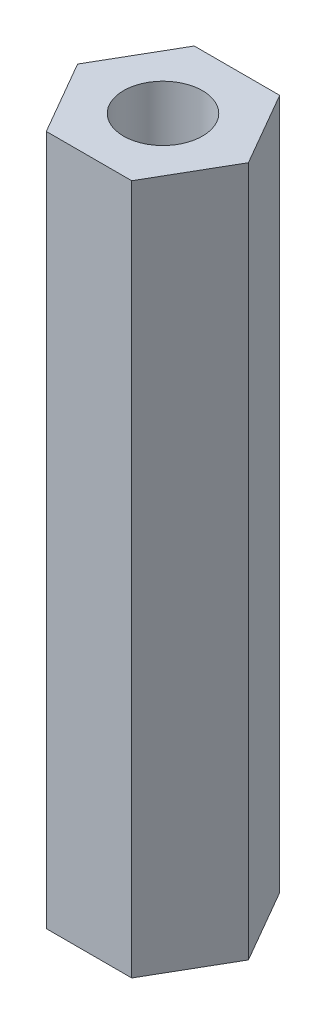
SolidWorks part; units mm, degrees
ref_plane "Front Plane" through (0, 0, 0) normal (0, 0, 1) x (1, 0, 0)
ref_plane "Top Plane" through (0, 0, 0) normal (0, 1, 0) x (1, 0, 0)
ref_plane "Right Plane" through (0, 0, 0) normal (1, 0, 0) x (0, 0, -1)
sketch "Sketch1" plane through (0, 0, 0) normal (0, 1, 0) x (1, 0, 0)
  line L1 (2.1651, 3.75) -> (-2.1651, 3.75)
  line L2 (-2.1651, 3.75) -> (-4.3301, 0)
  line L3 (-4.3301, 0) -> (-2.1651, -3.75)
  line L4 (-2.1651, -3.75) -> (2.1651, -3.75)
  line L5 (2.1651, -3.75) -> (4.3301, 0)
  line L6 (4.3301, 0) -> (2.1651, 3.75)
  circle A0 centre (0, 0) radius 3.75 construction
  circle A1 centre (0, 0) radius 2
  dimension "D1" = 7.5
  dimension "D2" = 4
extrude "Boss-Extrude1" add sketch "Sketch1" along normal blind 35
